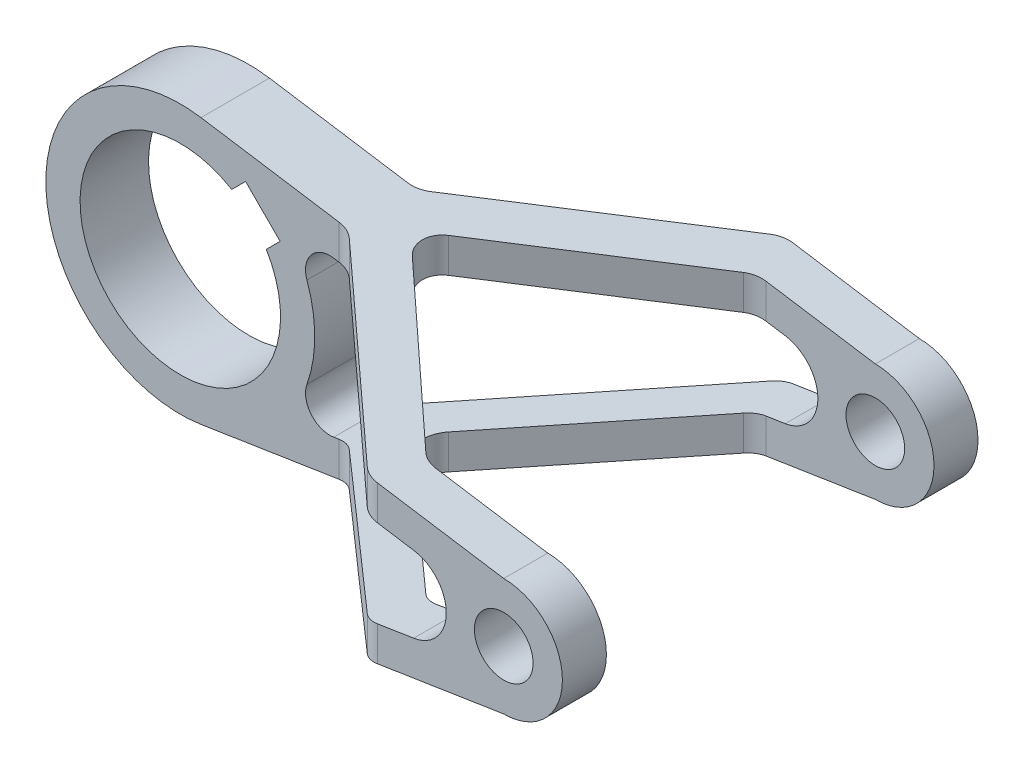
SolidWorks part; units mm, degrees
material "1060 Alaşım"
ref_plane "Ön Düzlem" through (0, 0, 0) normal (0, 0, 1) x (1, 0, 0)
ref_plane "Üst Düzlem" through (0, 0, 0) normal (0, 1, 0) x (1, 0, 0)
ref_plane "Sağ Düzlem" through (0, 0, 0) normal (1, 0, 0) x (0, 0, -1)
sketch "Çizim2" plane through (0, 0, 0) normal (0, 1, 0) x (1, 0, 0)
  line L0 (0.8355, 6.6645) -> (40.718, 42.5) construction
  line L1 (-60.7075, -7) -> (-0.7075, -7)
  line L2 (-60.7075, -7) -> (-60.7075, 7)
  line L3 (-60.7075, 7) -> (-0.7075, 7)
  line L5 (2.6343, 8.2808) -> (39.2925, 41.2192)
  line L6 (42.6343, 42.5) -> (80.4464, 42.5)
  line L7 (10.994, 3.6928) -> (42.742, 32.2192)
  line L8 (46.0838, 33.5) -> (80.4464, 33.5)
  line L9 (80.4464, 33.5) -> (80.4464, 42.5)
  line L10 (-78.8215, 0) -> (0.9464, 0) construction
  line L11 (80.4464, -33.5) -> (80.4464, -42.5)
  line L12 (45.5773, -33.5) -> (80.4464, -33.5)
  line L13 (10.9678, -3.7218) -> (42.2093, -32.1954)
  line L14 (42.6003, -42.5) -> (80.4464, -42.5)
  line L15 (2.6361, -8.2824) -> (39.2568, -41.2176)
  line L16 (6.8842, 0) -> (63.4957, 0) construction
  line L17 (6.8507, -0.0301) -> (44.1674, 33.5) construction
  line L18 (40.718, 42.5) -> (80.4464, 42.5) construction
  line L19 (44.1674, 33.5) -> (80.4464, 33.5) construction
  arc A0 (-0.7075, 7) -> (2.6343, 8.2808) centre (-0.7075, 12) ccw
  arc A1 (-0.7075, -7) -> (2.6361, -8.2824) centre (-0.7075, -12) cw
  arc A2 (39.2568, -41.2176) -> (42.6003, -42.5) centre (42.6003, -37.5) ccw
  arc A3 (39.2925, 41.2192) -> (42.6343, 42.5) centre (42.6343, 37.5) cw
  arc A4 (42.2093, -32.1954) -> (45.5773, -33.5) centre (45.5773, -28.5) ccw
  arc A5 (42.742, 32.2192) -> (46.0838, 33.5) centre (46.0838, 28.5) cw
  arc A6 (10.994, 3.6928) -> (10.9678, -3.7218) centre (14.3358, -0.0264) ccw
  point P4 (-60.7075, 0)
  point P10 (0.9464, 0)
  point P28 (40.6826, -42.5)
  point P34 (43.6406, -33.5)
  dimension "D3" = 5
  dimension "D4" = 5
  dimension "D1" = 5
  dimension "D2" = 9
  dimension "D5" = 85
  dimension "D6" = 60
  dimension "D7" = 100
  dimension "D8" = 14
extrude "Yükseklik-Ekstrüzyon1" add sketch "Çizim2" along normal blind 55
sketch "Çizim4" plane through (0, 0, 0) normal (0, 0, 1) x (1, 0, 0)
  line L0 (80.4464, 55) -> (80.4464, 0) construction
  line L1 (-60.7075, 55) -> (-60.7075, 0) construction
  line L2 (68.4464, 39.5) -> (-28.9756, 54.6724)
  line L3 (68.4464, 15.5) -> (-28.9756, 0.3276)
  line L5 (80.4464, 55) -> (-60.7075, 55)
  line L6 (80.4464, 55) -> (80.4464, 0)
  line L7 (80.4464, 0) -> (-60.7075, 0)
  line L8 (-60.7075, 55) -> (-60.7075, 0)
  circle A0 centre (68.4464, 27.5) radius 12
  circle A1 centre (68.4464, 27.5) radius 6
  circle A2 centre (-33.2075, 27.5) radius 27.5
  circle A3 centre (-33.2075, 27.5) radius 20.5
  dimension "D1" = 7
extrude "Kes-Ekstrüzyon1" cut sketch "Çizim4" against normal blind 55 and the other way blind 55 contours A2 L2 A0 L6 L5 | A2 L7 L6 A0 L3 | A2 L5 L8 | A2 L8 L7 | A3 | A1
sketch "Çizim7" plane through (0, 0, 0) normal (0, 0, 1) x (1, 0, 0)
  line L0 (-5.7075, 27.5) -> (68.4464, 27.5) construction
  line L1 (-33.2075, 27.5) -> (-33.2075, 80.9957) construction
  line L2 (-33.2075, 27.5) -> (0.5652, 61.2727) construction
  line L3 (-15.614, 38.0224) -> (-12.7856, 40.8508)
  line L4 (-12.7856, 40.8508) -> (-19.8566, 47.9219)
  line L5 (-19.8566, 47.9219) -> (-22.6851, 45.0934)
  circle A1 centre (-33.2075, 27.5) radius 20.5 construction
  arc A2 (-15.614, 38.0224) -> (-22.6851, 45.0934) centre (-33.2075, 27.5) ccw
  point P12 (-16.3211, 44.3863)
  dimension "D1" = 45
extrude "Kes-Ekstrüzyon2" cut sketch "Çizim7" against normal blind 55 and the other way blind 55
sketch "Çizim8" plane through (0, 0, 0) normal (0, 0, 1) x (1, 0, 0)
  line L24 (-30.0528, 7.2442) -> (-1.7846, 11.6466)
  line L25 (-1.7846, 11.6466) -> (1.5589, 12.1674)
  line L26 (1.5589, 12.1674) -> (38.1796, 17.8706)
  line L27 (38.1796, 17.8706) -> (41.5231, 18.3914)
  line L28 (41.5231, 18.3914) -> (67.3692, 22.4166)
  line L29 (-1.8274, 11.64) -> (-1.7846, 11.6466)
  line L30 (-1.7846, 11.6466) -> (1.5589, 12.1674)
  line L31 (1.5589, 12.1674) -> (38.1796, 17.8706)
  line L32 (38.1796, 17.8706) -> (41.5231, 18.3914)
  line L33 (41.5231, 18.3914) -> (50.0294, 19.7161)
  line L71 (67.3692, 32.5834) -> (41.5231, 36.6086)
  line L72 (41.5231, 36.6086) -> (38.1796, 37.1294)
  line L73 (38.1796, 37.1294) -> (1.5589, 42.8326)
  line L74 (1.5589, 42.8326) -> (-1.7846, 43.3534)
  line L75 (-1.7846, 43.3534) -> (-30.0528, 47.7558)
  line L76 (50.0294, 35.2839) -> (41.5231, 36.6086)
  line L77 (41.5231, 36.6086) -> (38.1796, 37.1294)
  line L78 (38.1796, 37.1294) -> (1.5589, 42.8326)
  line L79 (1.5589, 42.8326) -> (-1.7846, 43.3534)
  line L80 (-1.7846, 43.3534) -> (-1.8274, 43.36)
  arc A0 (-7.3061, 18.2604) -> (-7.3061, 36.7396) centre (-33.2075, 27.5) ccw
  arc A1 (-7.3061, 18.2604) -> (-1.8274, 11.64) centre (-2.5968, 16.5804) ccw
  arc A2 (-7.3061, 36.7396) -> (-1.8274, 43.36) centre (-2.5968, 38.4196) cw
  arc A3 (50.0294, 19.7161) -> (50.0294, 35.2839) centre (48.8172, 27.5) ccw
  dimension "D3" = 5
  dimension "D1" = 7
  dimension "D2" = 7
extrude "Kes-Ekstrüzyon3" cut sketch "Çizim8" against normal through all and the other way through all
